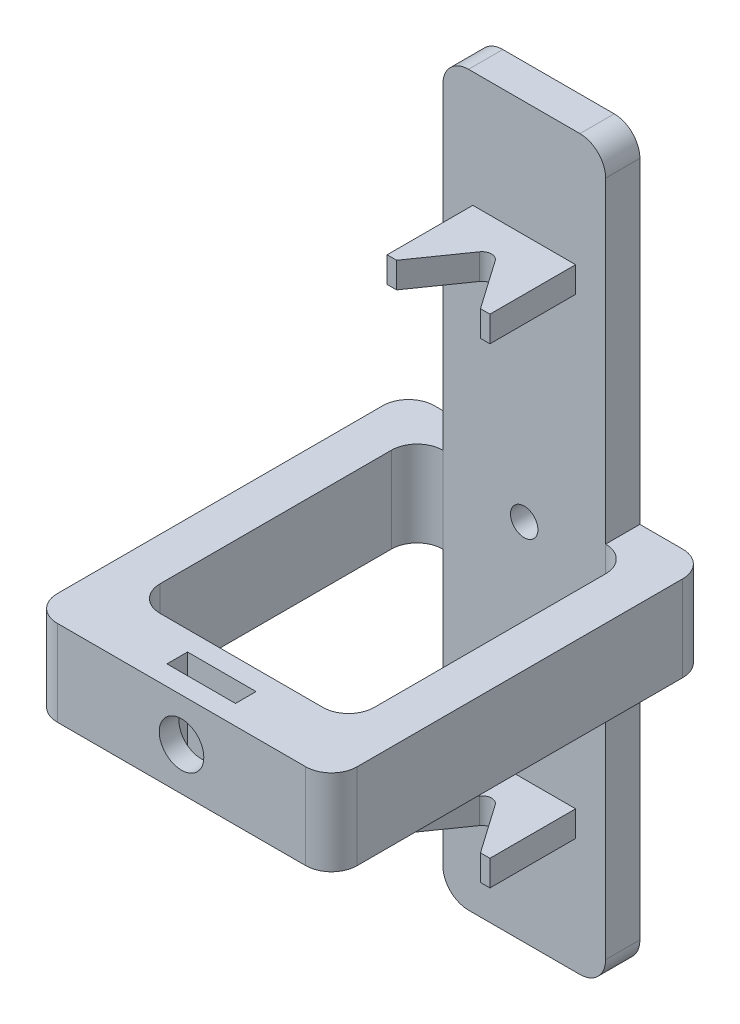
SolidWorks part; units mm, degrees
ref_plane "Front Plane" through (0, 0, 0) normal (0, 0, 1) x (1, 0, 0)
ref_plane "Top Plane" through (0, 0, 0) normal (0, 1, 0) x (1, 0, 0)
ref_plane "Right Plane" through (0, 0, 0) normal (1, 0, 0) x (0, 0, -1)
sketch "Sketch1" plane through (0, 0, 0) normal (0, 0, 1) x (1, 0, 0)
  line L1 (-7.5, 42.5) -> (7.5, 42.5)
  line L2 (-7.5, 42.5) -> (-7.5, -42.5)
  line L3 (-7.5, -42.5) -> (7.5, -42.5)
  line L4 (7.5, 42.5) -> (7.5, -42.5)
  line L5 (-7.5, 42.5) -> (7.5, -42.5) construction
  line L6 (-7.5, -42.5) -> (7.5, 42.5) construction
  point P0 (0, 0)
  dimension "D1" = 85
  dimension "D2" = 15
extrude "Boss-Extrude1" add sketch "Sketch1" along normal blind 4
sketch "Sketch2" plane through (0, 0, 4) normal (0, 0, 1) x (1, 0, 0)
  line L0 (0, 42.5) -> (0, 27.5)
  line L1 (0, -42.5) -> (0, -27.5)
  line L3 (-6, 29) -> (6, 29)
  line L4 (7.5, -42.5) -> (7.5, 42.5)
  line L5 (7.5, 42.5) -> (-7.5, 42.5)
  line L6 (-7.5, 42.5) -> (-7.5, -42.5)
  line L7 (-7.5, -42.5) -> (7.5, -42.5)
  line L9 (7.5, 42.5) -> (-7.5, 42.5)
  line L11 (-7.5, -42.5) -> (7.5, -42.5)
  line L12 (-6, 29) -> (-6, 26)
  line L13 (-6, 26) -> (6, 26)
  line L14 (6, 29) -> (6, 26)
  line L15 (-6, 29) -> (6, 26) construction
  line L16 (-6, 26) -> (6, 29) construction
  line L17 (-6, -29) -> (6, -29)
  line L18 (-6, -29) -> (-6, -26)
  line L19 (-6, -26) -> (6, -26)
  line L20 (6, -29) -> (6, -26)
  line L21 (-6, -29) -> (6, -26) construction
  line L22 (-6, -26) -> (6, -29) construction
  dimension "D2" = 15
  dimension "D3" = 15
  dimension "D4" = 3
  dimension "D5" = 12
  dimension "D6" = 3
  dimension "D7" = 12
  dimension "D1" = 0
extrude "Boss-Extrude2" add sketch "Sketch2" along normal blind 10
sketch "Sketch3" plane through (0, 29, 0) normal (0, 1, 0) x (1, 0, 0)
  line L0 (0, -14) -> (0, -7)
  line L1 (-0.9046, -8.2934) -> (-4.896, -14)
  line L2 (0.9046, -8.2934) -> (4.896, -14)
  line L4 (6, -4) -> (-6, -4)
  line L5 (-6, -4) -> (-6, -14)
  line L6 (-6, -14) -> (6, -14)
  line L7 (6, -14) -> (6, -4)
  line L8 (6, -4) -> (-6, -4)
  line L9 (-6, -4) -> (-6, -12.896)
  line L10 (-4.896, -14) -> (4.896, -14)
  line L11 (6, -12.896) -> (6, -4)
  arc A0 (6, -12.896) -> (4.896, -14) centre (4.896, -12.896) cw
  arc A1 (-4.896, -14) -> (-6, -12.896) centre (-4.896, -12.896) cw
  arc A2 (0.9046, -8.2934) -> (-0.9046, -8.2934) centre (0, -8.9261) ccw
  line M9 (-6, -14) -> (6, -14)
  dimension "D2" = 1.104
  dimension "D4" = 1.104
  dimension "D3" = 7
  dimension "D1" = 0
extrude "Cut-Extrude1" cut sketch "Sketch3" against normal blind 60 contours L2 A2 L0 M9 | L0 A2 L1 M9
sketch "Sketch4" plane through (0, 0, 4) normal (0, 0, 1) x (1, 0, 0)
  line L0 (0, 0) -> (0, -15.4)
  circle A0 centre (0, -15.4) radius 1.6
  circle A1 centre (0, 0) radius 1.6
  dimension "D2" = 3.2
  dimension "D3" = 3.2
  dimension "D1" = 15.4
extrude "Cut-Extrude2" cut sketch "Sketch4" against normal blind 4
sketch "Sketch5" plane through (0, 42.5, 0) normal (0, 1, 0) x (1, 0, 0)
  line L1 (7.5, 0) -> (17.5, 0)
  line L2 (7.5, 0) -> (7.5, -4)
  line L3 (7.5, -4) -> (17.5, -4)
  line L4 (17.5, 0) -> (17.5, -4)
  line L5 (-7.5, 0) -> (-17.5, 0)
  line L6 (-7.5, 0) -> (-7.5, -4)
  line L7 (-7.5, -4) -> (-17.5, -4)
  line L8 (-17.5, 0) -> (-17.5, -4)
  dimension "D1" = 10
  dimension "D2" = 10
  dimension "D3" = 4
  dimension "D4" = 4
extrude "Boss-Extrude3" add sketch "Sketch5" against normal blind 50
sketch "Sketch8" plane through (0, 0, 4) normal (0, 0, 1) x (1, 0, 0)
  line L1 (17.5, 42.5) -> (7.5, 42.5)
  line L2 (17.5, 42.5) -> (17.5, 2.5)
  line L3 (17.5, 2.5) -> (7.5, 2.5)
  line L4 (7.5, 42.5) -> (7.5, 2.5)
  line L5 (-17.5, 42.5) -> (-7.5, 42.5)
  line L6 (-17.5, 42.5) -> (-17.5, 2.5)
  line L7 (-17.5, 2.5) -> (-7.5, 2.5)
  line L8 (-7.5, 42.5) -> (-7.5, 2.5)
  dimension "D1" = 40
  dimension "D2" = 10
  dimension "D3" = 40
  dimension "D4" = 10
extrude "Cut-Extrude3" cut sketch "Sketch8" against normal blind 4
sketch "Sketch10" plane through (0, 0, 4) normal (0, 0, 1) x (1, 0, 0)
  line L1 (17.5, 2.5) -> (7.5, 2.5)
  line L2 (17.5, 2.5) -> (17.5, -7.5)
  line L3 (17.5, -7.5) -> (7.5, -7.5)
  line L4 (7.5, 2.5) -> (7.5, -7.5)
  line L5 (-17.5, 2.5) -> (-7.5, 2.5)
  line L6 (-17.5, 2.5) -> (-17.5, -7.5)
  line L7 (-17.5, -7.5) -> (-7.5, -7.5)
  line L8 (-7.5, 2.5) -> (-7.5, -7.5)
extrude "Boss-Extrude4" add sketch "Sketch10" along normal blind 40
sketch "Sketch11" plane through (7.5, 0, 0) normal (-1, 0, 0) x (0, 0, 1)
  line L1 (44, 2.5) -> (37, 2.5)
  line L2 (44, 2.5) -> (44, -7.5)
  line L3 (44, -7.5) -> (37, -7.5)
  line L4 (37, 2.5) -> (37, -7.5)
  dimension "D1" = 10
  dimension "D2" = 7
extrude "Boss-Extrude5" add sketch "Sketch11" along normal up to surface (15 mm away) up to face at (-7.5, -2.5, 24)
sketch "Sketch13" plane through (0, 2.5, 0) normal (0, 1, 0) x (1, 0, 0)
  line L3 (-7.5, -4) -> (-12.5, -4)
  line L4 (-7.5, -4) -> (-7.5, -37)
  line L5 (-7.5, -37) -> (-12.5, -37)
  line L6 (-12.5, -4) -> (-12.5, -37)
  line L7 (7.5, -4) -> (12.5, -4)
  line L8 (7.5, -4) -> (7.5, -37)
  line L9 (7.5, -37) -> (12.5, -37)
  line L10 (12.5, -4) -> (12.5, -37)
  dimension "D1" = 33
  dimension "D2" = 5
  dimension "D3" = 33
  dimension "D4" = 5
extrude "Cut-Extrude4" cut sketch "Sketch13" against normal blind 10
sketch "Sketch14" plane through (0, 0, 44) normal (0, 0, 1) x (1, 0, 0)
  line L0 (0, -7.5) -> (0, 2.5)
  line L1 (-17.5, -7.5) -> (17.5, -7.5) construction
  line L2 (17.5, 2.5) -> (-17.5, 2.5) construction
  circle A0 centre (0, -2.5) radius 2.6
  dimension "D1" = 5.2
extrude "Cut-Extrude6" cut sketch "Sketch14" against normal up to surface (7 mm away) contours L0 A0 | L0 A0 up to face at (0, -2.5, 37)
sketch "Sketch17" plane through (7.5, 0, 0) normal (1, 0, 0) x (0, 0, -1)
  line L4 (0, -42.5) -> (0, -7.5)
  line L5 (0, -7.5) -> (-4, -7.5)
  line L6 (-4, -7.5) -> (-4, -42.5)
  line L7 (-4, -42.5) -> (0, -42.5)
  line L8 (0, -42.5) -> (0, -7.5)
  line L9 (0, -7.5) -> (-4, -7.5)
  line L10 (-4, -7.5) -> (-4, -42.5)
  line L11 (-4, -42.5) -> (0, -42.5)
  line L12 (-4, 42.5) -> (-4, 2.5)
  line L13 (-4, 2.5) -> (0, 2.5)
  line L14 (0, 2.5) -> (0, 42.5)
  line L15 (0, 42.5) -> (-4, 42.5)
  line L16 (-4, 42.5) -> (-4, 2.5)
  line L17 (-4, 2.5) -> (0, 2.5)
  line L18 (0, 2.5) -> (0, 42.5)
  line L19 (0, 42.5) -> (-4, 42.5)
  dimension "D1" = 0
  dimension "D2" = 0
extrude "Boss-Extrude6" add sketch "Sketch17" along normal blind 2
sketch "Sketch18" plane through (-7.5, 0, 0) normal (-1, 0, 0) x (0, 0, 1)
  line L4 (4, -42.5) -> (4, -7.5)
  line L5 (4, -7.5) -> (0, -7.5)
  line L6 (0, -7.5) -> (0, -42.5)
  line L7 (0, -42.5) -> (4, -42.5)
  line L8 (4, -42.5) -> (4, -7.5)
  line L9 (4, -7.5) -> (0, -7.5)
  line L10 (0, -7.5) -> (0, -42.5)
  line L11 (0, -42.5) -> (4, -42.5)
  line L12 (4, 2.5) -> (4, 42.5)
  line L13 (4, 42.5) -> (0, 42.5)
  line L14 (0, 42.5) -> (0, 2.5)
  line L15 (0, 2.5) -> (4, 2.5)
  line L16 (4, 2.5) -> (4, 42.5)
  line L17 (4, 42.5) -> (0, 42.5)
  line L18 (0, 42.5) -> (0, 2.5)
  line L19 (0, 2.5) -> (4, 2.5)
  dimension "D1" = 0
  dimension "D2" = 0
extrude "Boss-Extrude7" add sketch "Sketch18" along normal blind 2
fillet "Fillet2" radius 3 12 edges at (9.5, -42.5, 2) (-9.5, -42.5, 2) (9.5, 42.5, 2) (-9.5, 42.5, 2) (-17.5, -2.5, 0) (17.5, -2.5, 44) (17.5, -2.5, 0) (-17.5, -2.5, 44) (12.5, -2.5, 37) (-12.5, -2.5, 37) (12.5, -2.5, 4) (-12.5, -2.5, 4)
sketch "Sketch19" plane through (0, 2.5, 0) normal (0, 1, 0) x (1, 0, 0)
  line L0 (0, -44) -> (0, -37)
  line L1 (14.5, -44) -> (-14.5, -44) construction
  line L2 (-9.5, -37) -> (9.5, -37) construction
  line L4 (-4, -39.3) -> (4, -39.3)
  line L5 (-4, -39.3) -> (-4, -41.7)
  line L6 (-4, -41.7) -> (4, -41.7)
  line L7 (4, -39.3) -> (4, -41.7)
  line L8 (-4, -39.3) -> (4, -41.7) construction
  line L9 (-4, -41.7) -> (4, -39.3) construction
  point P6 (0, -40.5)
  dimension "D1" = 2.4
  dimension "D2" = 8
extrude "Cut-Extrude7" cut sketch "Sketch19" against normal blind 10 contours L5 L6 L0 L4 | L7 L4 L0 L6
